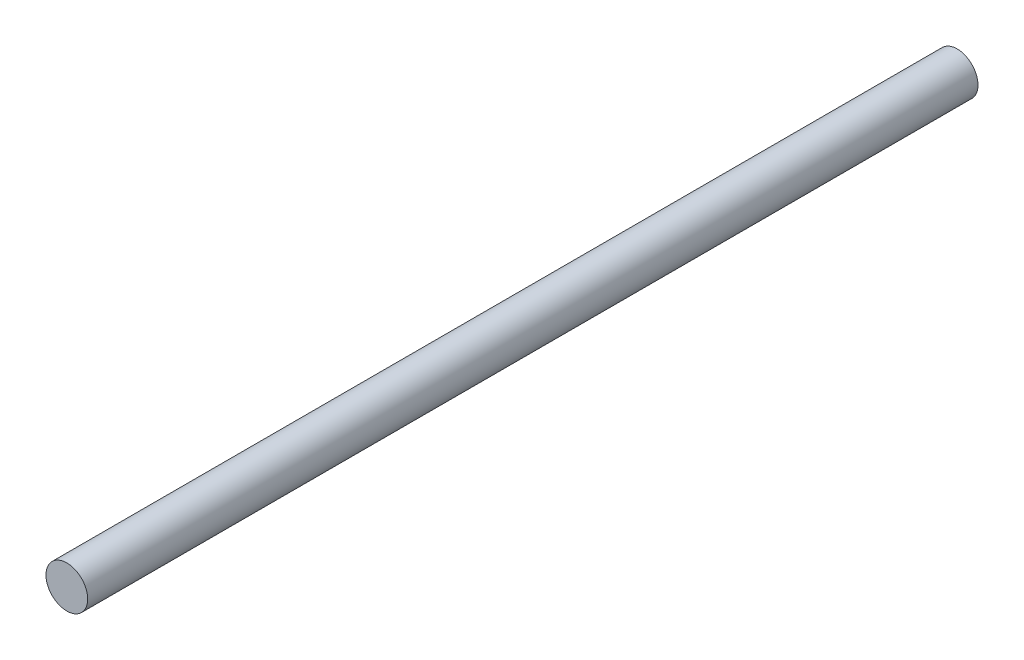
SolidWorks part; units mm, degrees
ref_plane "Front Plane" through (0, 0, 0) normal (0, 0, 1) x (1, 0, 0)
ref_plane "Top Plane" through (0, 0, 0) normal (0, 1, 0) x (1, 0, 0)
ref_plane "Right Plane" through (0, 0, 0) normal (1, 0, 0) x (0, 0, -1)
other "Default"
sketch "Sketch1" plane through (0, 0, 0) normal (0, 0, 1) x (1, 0, 0)
  circle A0 centre (0, 0) radius 4.7625
  dimension "Diameter" = 9.525
extrude "Boss-Extrude1" add sketch "Sketch1" along normal blind 203.2
